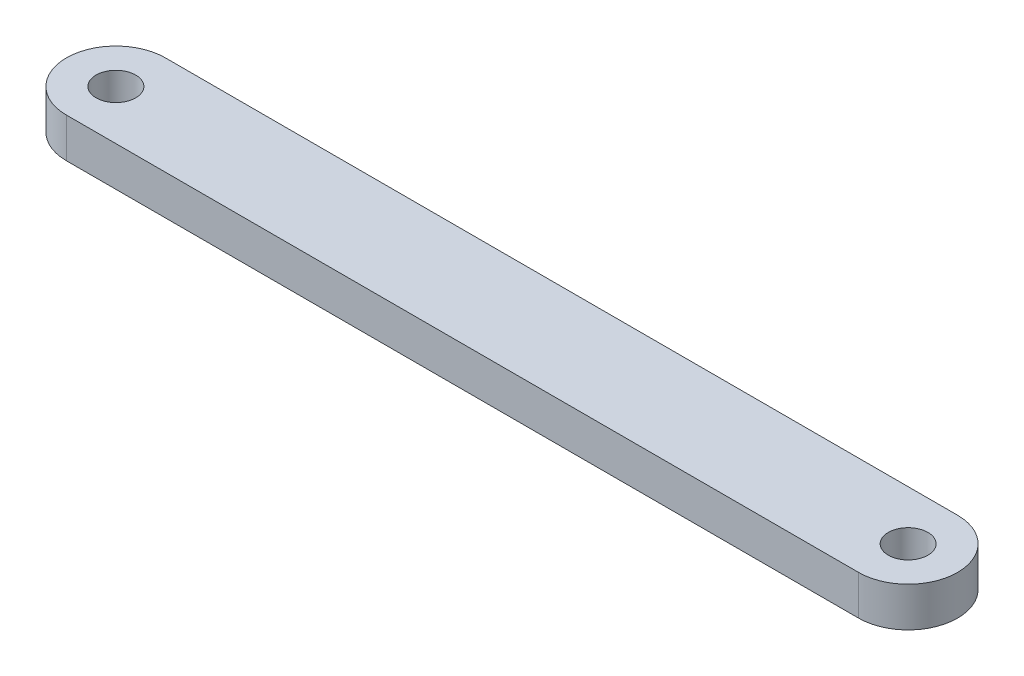
SolidWorks part; units mm, degrees
ref_plane "Front Plane" through (0, 0, 0) normal (0, 0, 1) x (1, 0, 0)
ref_plane "Top Plane" through (0, 0, 0) normal (0, 1, 0) x (1, 0, 0)
ref_plane "Right Plane" through (0, 0, 0) normal (1, 0, 0) x (0, 0, -1)
sketch "Sketch1" plane through (0, 0, 0) normal (0, 1, 0) x (1, 0, 0)
  line L0 (-10, 0) -> (30, 0) construction
  line L1 (-10, 2.5) -> (30, 2.5)
  line L2 (-10, -2.5) -> (30, -2.5)
  arc A0 (-10, 2.5) -> (-10, -2.5) centre (-10, 0) ccw
  arc A1 (30, -2.5) -> (30, 2.5) centre (30, 0) ccw
  circle A2 centre (30, 0) radius 1
  circle A3 centre (-10, 0) radius 1
  point P3 (10, 0)
  dimension "D3" = 2
  dimension "D4" = 2.5
  dimension "D5" = 2
  dimension "D1" = 40
  dimension "D12" = 10
extrude "Boss-Extrude1" add sketch "Sketch1" along normal blind 2
